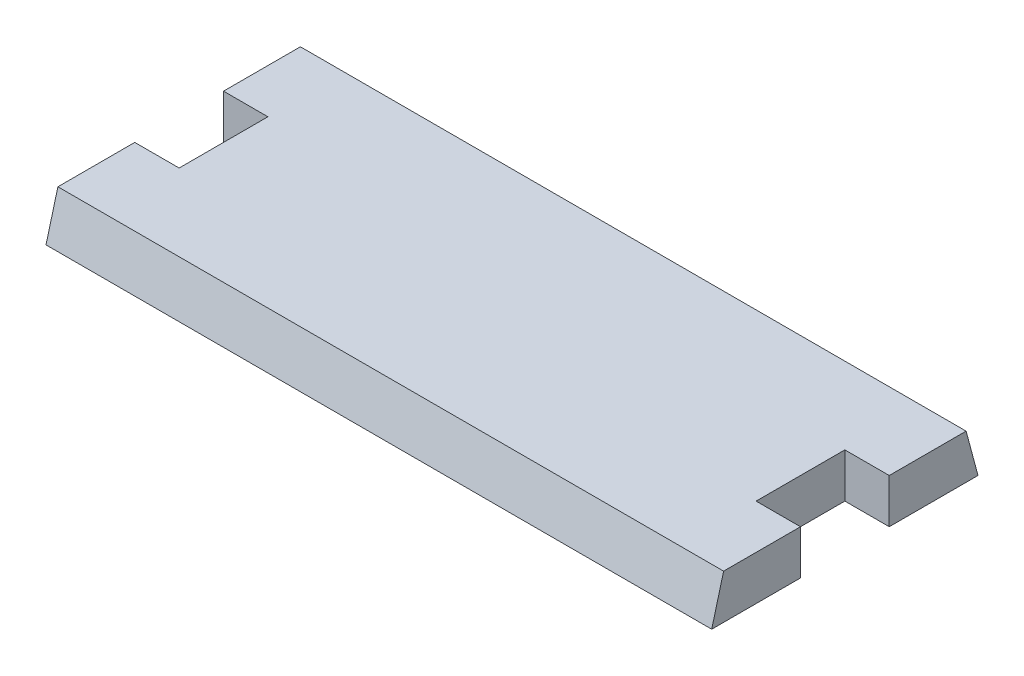
SolidWorks part; units mm, degrees
ref_plane "Front Plane" through (0, 0, 0) normal (0, 0, 1) x (1, 0, 0)
ref_plane "Top Plane" through (0, 0, 0) normal (0, 1, 0) x (1, 0, 0)
ref_plane "Right Plane" through (0, 0, 0) normal (1, 0, 0) x (0, 0, -1)
sketch "Sketch1" plane through (0, 0, 0) normal (0, 1, 0) x (1, 0, 0)
  line L0 (75, -10) -> (75, -30)
  line L1 (-75, 30) -> (75, 30)
  line L2 (-75, 30) -> (-75, 10)
  line L3 (-75, -30) -> (75, -30)
  line L4 (75, 30) -> (75, 10)
  line L5 (-75, 30) -> (75, -30) construction
  line L6 (-75, -30) -> (75, 30) construction
  line L7 (75, 10) -> (65, 10)
  line L9 (75, -10) -> (65, -10)
  line L10 (65, 10) -> (65, -10)
  line L11 (0, 0) -> (0, 47.7717) construction
  line L12 (75, 30) -> (75, -30)
  line L13 (-75, -10) -> (-75, -30)
  line L14 (-75, -10) -> (-65, -10)
  line L15 (-65, 10) -> (-65, -10)
  line L16 (-75, 10) -> (-65, 10)
  line L17 (-75, 30) -> (-75, 10)
  line L18 (-75, -10) -> (-75, -30)
  point P0 (0, 0)
  dimension "D1" = 150
  dimension "D2" = 60
  dimension "D3" = 10
  dimension "D4" = 20
  dimension "D5" = 20
extrude "Boss-Extrude1" add sketch "Sketch1" along normal blind 10 contours L2 L16 L15 L14 L13 L3 L0 L9 L10 L7 L4 L1
draft "Draft1" type of draft neutral plane draft angle 15 faces to draft 2 face at (0, 5, -30) face at (0, 5, 30) neutral plane through (0, 0, 0) neutral plane normal (0, -1, 0) reverse direction yes parameters "D1"=15
